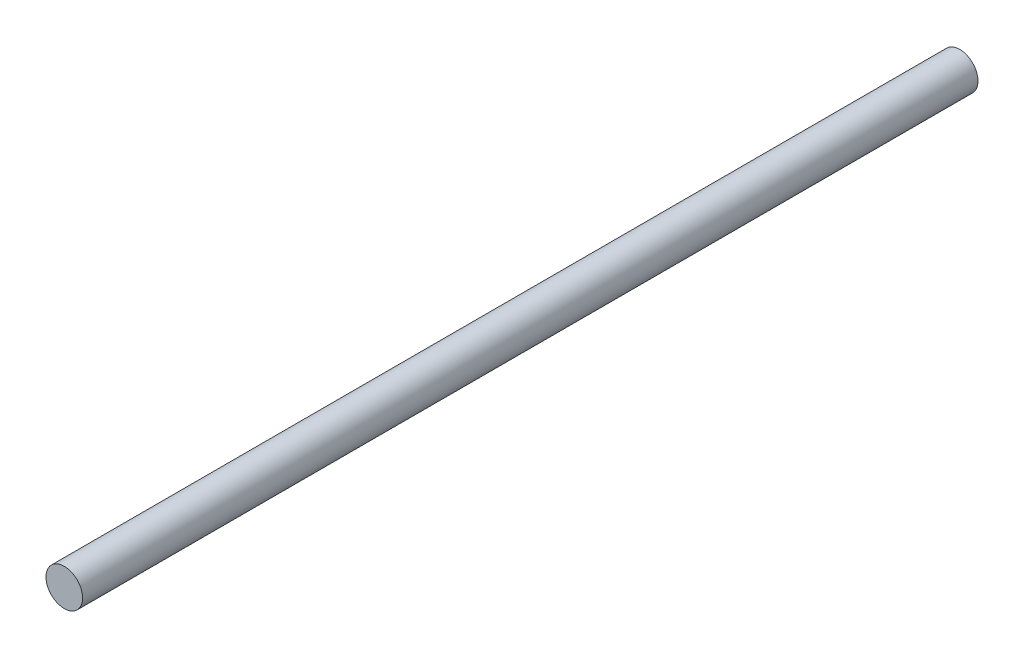
SolidWorks part; units mm, degrees
ref_plane "Front Plane" through (0, 0, 0) normal (0, 0, 1) x (1, 0, 0)
ref_plane "Top Plane" through (0, 0, 0) normal (0, 1, 0) x (1, 0, 0)
ref_plane "Right Plane" through (0, 0, 0) normal (1, 0, 0) x (0, 0, -1)
sketch "Sketch1" plane through (0, 0, 0) normal (0, 0, 1) x (1, 0, 0)
  circle A0 centre (0, 0) radius 3.81
  dimension "D1" = 7.62
extrude "Boss-Extrude1" add sketch "Sketch1" along normal blind 186.182
